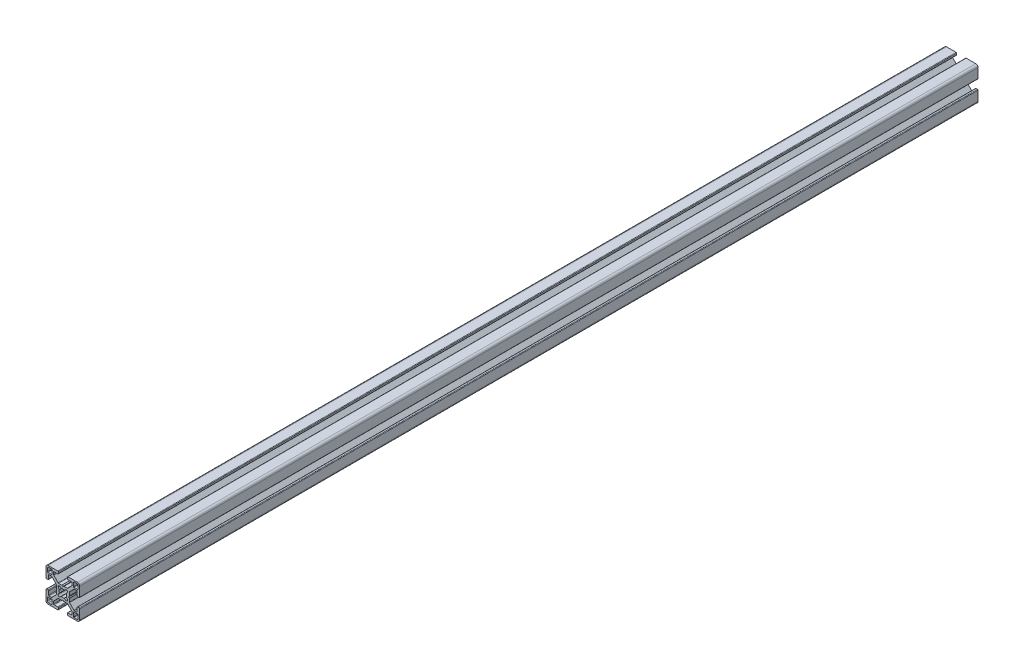
SolidWorks part; units mm, degrees
ref_plane "Front" through (0, 0, 0) normal (0, 0, 1) x (1, 0, 0)
ref_plane "Top" through (0, 0, 0) normal (0, 1, 0) x (1, 0, 0)
ref_plane "Right" through (0, 0, 0) normal (1, 0, 0) x (0, 0, -1)
ref_plane "Plane1" through (0, 0, -25) normal (0, 0, -1) x (-1, 0, 0)
sketch "Sketch1" plane through (0, 0, -25) normal (0, 0, -1) x (-1, 0, 0)
  line L0 (13.7, -9.881) -> (13.7, -12.7)
  line L1 (12.7, -13.7) -> (9.881, -13.7)
  line L2 (9.5, -13.319) -> (9.5, -9.881)
  line L3 (9.881, -9.5) -> (13.319, -9.5)
  line L4 (13.7, 12.7) -> (13.7, 9.881)
  line L5 (13.319, 9.5) -> (9.881, 9.5)
  line L6 (9.5, 9.881) -> (9.5, 13.319)
  line L7 (9.881, 13.7) -> (12.7, 13.7)
  line L8 (3.0544, -1.3138) -> (4.0107, -2.5139)
  line L9 (2.5139, -4.0107) -> (1.3138, -3.0544)
  line L10 (-1.3138, -3.0544) -> (-2.5139, -4.0107)
  line L11 (-4.0107, -2.5139) -> (-3.0544, -1.3138)
  line L12 (-3.0544, 1.3138) -> (-4.0107, 2.5139)
  line L13 (-2.5139, 4.0107) -> (-1.3138, 3.0544)
  line L14 (1.3138, 3.0544) -> (2.5139, 4.0107)
  line L15 (4.0107, 2.5139) -> (3.0544, 1.3138)
  line L16 (-9.5, 13.319) -> (-9.5, 9.881)
  line L17 (-9.881, 9.5) -> (-13.319, 9.5)
  line L18 (-13.7, 9.881) -> (-13.7, 12.7)
  line L19 (-12.7, 13.7) -> (-9.881, 13.7)
  line L20 (-9.5, -9.881) -> (-9.5, -13.319)
  line L21 (-9.881, -13.7) -> (-12.7, -13.7)
  line L22 (-13.7, -12.7) -> (-13.7, -9.881)
  line L23 (-13.319, -9.5) -> (-9.881, -9.5)
  line L24 (15, -13) -> (15, -4.508)
  line L25 (14.492, -4) -> (13.251, -4)
  line L26 (12.743, -4.508) -> (12.743, -7.742)
  line L27 (12.235, -8.25) -> (10.2629, -8.25)
  line L28 (9.9037, -8.1012) -> (5.9833, -4.1808)
  line L29 (5.8345, -3.8216) -> (5.8345, -0.949)
  line L30 (5.8345, -0.949) -> (5.325, 0)
  line L31 (5.325, 0) -> (5.8345, 0.949)
  line L32 (5.8345, 0.949) -> (5.8345, 3.8203)
  line L33 (5.9833, 4.1795) -> (9.905, 8.1012)
  line L34 (10.2642, 8.25) -> (12.235, 8.25)
  line L35 (12.743, 7.742) -> (12.743, 4.508)
  line L36 (13.251, 4) -> (14.492, 4)
  line L37 (15, 4.508) -> (15, 13)
  line L38 (13, 15) -> (4.508, 15)
  line L39 (4, 14.492) -> (4, 13.251)
  line L40 (4.508, 12.743) -> (7.742, 12.743)
  line L41 (8.25, 12.235) -> (8.25, 10.2629)
  line L42 (8.1012, 9.9037) -> (4.1808, 5.9833)
  line L43 (3.8216, 5.8345) -> (0.949, 5.8345)
  line L44 (0.949, 5.8345) -> (0, 5.325)
  line L45 (0, 5.325) -> (-0.949, 5.8345)
  line L46 (-0.949, 5.8345) -> (-3.8203, 5.8345)
  line L47 (-4.1795, 5.9833) -> (-8.1012, 9.905)
  line L48 (-8.25, 10.2642) -> (-8.25, 12.235)
  line L49 (-7.742, 12.743) -> (-4.508, 12.743)
  line L50 (-4, 13.251) -> (-4, 14.492)
  line L51 (-4.508, 15) -> (-13, 15)
  line L52 (-15, 13) -> (-15, 4.508)
  line L53 (-14.492, 4) -> (-13.251, 4)
  line L54 (-12.743, 4.508) -> (-12.743, 7.742)
  line L55 (-12.235, 8.25) -> (-10.2629, 8.25)
  line L56 (-9.9037, 8.1012) -> (-5.9833, 4.1808)
  line L57 (-5.8345, 3.8216) -> (-5.8345, 0.949)
  line L58 (-5.8345, 0.949) -> (-5.325, 0)
  line L59 (-5.325, 0) -> (-5.8345, -0.949)
  line L60 (-5.8345, -0.949) -> (-5.8345, -3.8203)
  line L61 (-5.9833, -4.1795) -> (-9.905, -8.1012)
  line L62 (-10.2642, -8.25) -> (-12.235, -8.25)
  line L63 (-12.743, -7.742) -> (-12.743, -4.508)
  line L64 (-13.251, -4) -> (-14.492, -4)
  line L65 (-15, -4.508) -> (-15, -13)
  line L66 (-13, -15) -> (-4.508, -15)
  line L67 (-4, -14.492) -> (-4, -13.251)
  line L68 (-4.508, -12.743) -> (-7.742, -12.743)
  line L69 (-8.25, -12.235) -> (-8.25, -10.2629)
  line L70 (-8.1012, -9.9037) -> (-4.1808, -5.9833)
  line L71 (-3.8216, -5.8345) -> (-0.949, -5.8345)
  line L72 (-0.949, -5.8345) -> (0, -5.325)
  line L73 (0, -5.325) -> (0.949, -5.8345)
  line L74 (0.949, -5.8345) -> (3.8203, -5.8345)
  line L75 (4.1795, -5.9833) -> (8.1012, -9.905)
  line L76 (8.25, -10.2642) -> (8.25, -12.235)
  line L77 (7.742, -12.743) -> (4.508, -12.743)
  line L78 (4, -13.251) -> (4, -14.492)
  line L79 (4.508, -15) -> (13, -15)
  arc A0 (13.7, -12.7) -> (12.7, -13.7) centre (12.7, -12.7) cw
  arc A1 (9.881, -13.7) -> (9.5, -13.319) centre (9.881, -13.319) cw
  arc A2 (9.5, -9.881) -> (9.881, -9.5) centre (9.881, -9.881) cw
  arc A3 (13.319, -9.5) -> (13.7, -9.881) centre (13.319, -9.881) cw
  arc A4 (13.7, 9.881) -> (13.319, 9.5) centre (13.319, 9.881) cw
  arc A5 (9.881, 9.5) -> (9.5, 9.881) centre (9.881, 9.881) cw
  arc A6 (9.5, 13.319) -> (9.881, 13.7) centre (9.881, 13.319) cw
  arc A7 (12.7, 13.7) -> (13.7, 12.7) centre (12.7, 12.7) cw
  arc A8 (4.0107, -2.5139) -> (2.5139, -4.0107) centre (3.142, -3.142) cw
  arc A9 (1.3138, -3.0544) -> (-1.3138, -3.0544) centre (0, 0) cw
  arc A10 (-2.5139, -4.0107) -> (-4.0107, -2.5139) centre (-3.142, -3.142) cw
  arc A11 (-3.0544, -1.3138) -> (-3.0544, 1.3138) centre (0, 0) cw
  arc A12 (-4.0107, 2.5139) -> (-2.5139, 4.0107) centre (-3.142, 3.142) cw
  arc A13 (-1.3138, 3.0544) -> (1.3138, 3.0544) centre (0, 0) cw
  arc A14 (2.5139, 4.0107) -> (4.0107, 2.5139) centre (3.142, 3.142) cw
  arc A15 (3.0544, 1.3138) -> (3.0544, -1.3138) centre (0, 0) cw
  arc A16 (-9.5, 9.881) -> (-9.881, 9.5) centre (-9.881, 9.881) cw
  arc A17 (-13.319, 9.5) -> (-13.7, 9.881) centre (-13.319, 9.881) cw
  arc A18 (-13.7, 12.7) -> (-12.7, 13.7) centre (-12.7, 12.7) cw
  arc A19 (-9.881, 13.7) -> (-9.5, 13.319) centre (-9.881, 13.319) cw
  arc A20 (-9.5, -13.319) -> (-9.881, -13.7) centre (-9.881, -13.319) cw
  arc A21 (-12.7, -13.7) -> (-13.7, -12.7) centre (-12.7, -12.7) cw
  arc A22 (-13.7, -9.881) -> (-13.319, -9.5) centre (-13.319, -9.881) cw
  arc A23 (-9.881, -9.5) -> (-9.5, -9.881) centre (-9.881, -9.881) cw
  arc A24 (15, -4.508) -> (14.492, -4) centre (14.492, -4.508) ccw
  arc A25 (13.251, -4) -> (12.743, -4.508) centre (13.251, -4.508) ccw
  arc A26 (12.743, -7.742) -> (12.235, -8.25) centre (12.235, -7.742) cw
  arc A27 (10.2629, -8.25) -> (9.9037, -8.1012) centre (10.2629, -7.742) cw
  arc A28 (5.9833, -4.1808) -> (5.8345, -3.8216) centre (6.3425, -3.8216) cw
  arc A29 (5.8345, 3.8203) -> (5.9833, 4.1795) centre (6.3425, 3.8203) cw
  arc A30 (9.905, 8.1012) -> (10.2642, 8.25) centre (10.2642, 7.742) cw
  arc A31 (12.235, 8.25) -> (12.743, 7.742) centre (12.235, 7.742) cw
  arc A32 (12.743, 4.508) -> (13.251, 4) centre (13.251, 4.508) ccw
  arc A33 (14.492, 4) -> (15, 4.508) centre (14.492, 4.508) ccw
  arc A34 (15, 13) -> (13, 15) centre (13, 13) ccw
  arc A35 (4.508, 15) -> (4, 14.492) centre (4.508, 14.492) ccw
  arc A36 (4, 13.251) -> (4.508, 12.743) centre (4.508, 13.251) ccw
  arc A37 (7.742, 12.743) -> (8.25, 12.235) centre (7.742, 12.235) cw
  arc A38 (8.25, 10.2629) -> (8.1012, 9.9037) centre (7.742, 10.2629) cw
  arc A39 (4.1808, 5.9833) -> (3.8216, 5.8345) centre (3.8216, 6.3425) cw
  arc A40 (-3.8203, 5.8345) -> (-4.1795, 5.9833) centre (-3.8203, 6.3425) cw
  arc A41 (-8.1012, 9.905) -> (-8.25, 10.2642) centre (-7.742, 10.2642) cw
  arc A42 (-8.25, 12.235) -> (-7.742, 12.743) centre (-7.742, 12.235) cw
  arc A43 (-4.508, 12.743) -> (-4, 13.251) centre (-4.508, 13.251) ccw
  arc A44 (-4, 14.492) -> (-4.508, 15) centre (-4.508, 14.492) ccw
  arc A45 (-13, 15) -> (-15, 13) centre (-13, 13) ccw
  arc A46 (-15, 4.508) -> (-14.492, 4) centre (-14.492, 4.508) ccw
  arc A47 (-13.251, 4) -> (-12.743, 4.508) centre (-13.251, 4.508) ccw
  arc A48 (-12.743, 7.742) -> (-12.235, 8.25) centre (-12.235, 7.742) cw
  arc A49 (-10.2629, 8.25) -> (-9.9037, 8.1012) centre (-10.2629, 7.742) cw
  arc A50 (-5.9833, 4.1808) -> (-5.8345, 3.8216) centre (-6.3425, 3.8216) cw
  arc A51 (-5.8345, -3.8203) -> (-5.9833, -4.1795) centre (-6.3425, -3.8203) cw
  arc A52 (-9.905, -8.1012) -> (-10.2642, -8.25) centre (-10.2642, -7.742) cw
  arc A53 (-12.235, -8.25) -> (-12.743, -7.742) centre (-12.235, -7.742) cw
  arc A54 (-12.743, -4.508) -> (-13.251, -4) centre (-13.251, -4.508) ccw
  arc A55 (-14.492, -4) -> (-15, -4.508) centre (-14.492, -4.508) ccw
  arc A56 (-15, -13) -> (-13, -15) centre (-13, -13) ccw
  arc A57 (-4.508, -15) -> (-4, -14.492) centre (-4.508, -14.492) ccw
  arc A58 (-4, -13.251) -> (-4.508, -12.743) centre (-4.508, -13.251) ccw
  arc A59 (-7.742, -12.743) -> (-8.25, -12.235) centre (-7.742, -12.235) cw
  arc A60 (-8.25, -10.2629) -> (-8.1012, -9.9037) centre (-7.742, -10.2629) cw
  arc A61 (-4.1808, -5.9833) -> (-3.8216, -5.8345) centre (-3.8216, -6.3425) cw
  arc A62 (3.8203, -5.8345) -> (4.1795, -5.9833) centre (3.8203, -6.3425) cw
  arc A63 (8.1012, -9.905) -> (8.25, -10.2642) centre (7.742, -10.2642) cw
  arc A64 (8.25, -12.235) -> (7.742, -12.743) centre (7.742, -12.235) cw
  arc A65 (4.508, -12.743) -> (4, -13.251) centre (4.508, -13.251) ccw
  arc A66 (4, -14.492) -> (4.508, -15) centre (4.508, -14.492) ccw
  arc A67 (13, -15) -> (15, -13) centre (13, -13) ccw
extrude "Boss-Extrude1" add sketch "Sketch1" against normal blind 800.1
